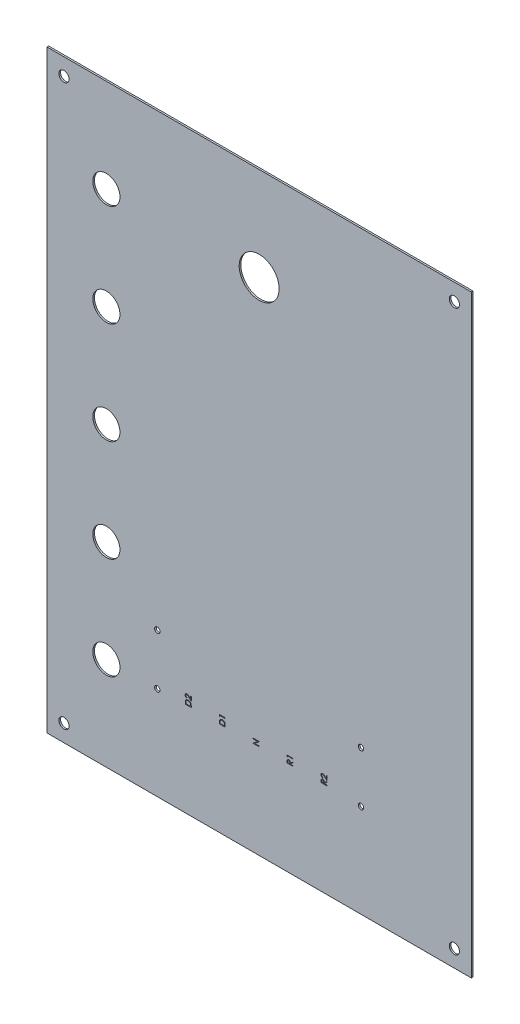
SolidWorks part; units mm, degrees
ref_plane "Front Plane" through (0, 0, 0) normal (1, 0, 0) x (0, 1, 0)
ref_plane "Top Plane" through (0, 0, 0) normal (0, 0, 1) x (0, 1, 0)
ref_plane "Right Plane" through (0, 0, 0) normal (0, 1, 0) x (-1, 0, 0)
sketch "Sketch1" plane through (0, 0, 0) normal (0, 0, 1) x (0, 1, 0)
  line L1 (-175, -125) -> (175, -125)
  line L2 (-175, -125) -> (-175, 125)
  line L3 (-175, 125) -> (175, 125)
  line L4 (175, -125) -> (175, 125)
  line L5 (-175, -125) -> (175, 125) construction
  line L6 (-175, 125) -> (175, -125) construction
  point P0 (0, 0)
  dimension "D1" = 350
  dimension "D2" = 250
extrude "Boss-Extrude1" add sketch "Sketch1" along normal blind 1
sketch "Sketch2" plane through (0, 0, 1) normal (0, 0, 1) x (0, -1, 0)
  line L0 (-160, -125) -> (-160, 125) construction
  line L1 (-175, -125) -> (175, -125) construction
  line L2 (175, 125) -> (-175, 125) construction
  line L3 (-175, 125) -> (-175, -125) construction
  circle A0 centre (-160, -60) radius 8
  circle A1 centre (-160, -30) radius 8
  circle A2 centre (-160, 0) radius 8
  circle A3 centre (-160, 30) radius 8
  circle A4 centre (-160, 60) radius 8
  dimension "D1" = 16
  dimension "D2" = 30
  dimension "D3" = 30
  dimension "D4" = 30
  dimension "D5" = 30
  dimension "D6" = 15
extrude "Cut-Extrude1" [suppressed] cut sketch "Sketch2" against normal through all
sketch "Sketch3" plane through (0, 0, 1) normal (0, 0, 1) x (0, -1, 0)
  line L0 (-175, -125) -> (175, -125) construction
  line L1 (-175, 125) -> (-175, -125) construction
  line L2 (0, 125) -> (0, -125) construction
  line L3 (175, 125) -> (-175, 125) construction
  line L4 (0, -125) -> (175, 0) construction
  line L5 (175, -125) -> (175, 125) construction
  line L6 (175, 0) -> (-175, 0) construction
  circle A0 centre (120, -90) radius 8
  circle A1 centre (60, -90) radius 8
  circle A2 centre (0, -90) radius 8
  circle A3 centre (-60, -90) radius 8
  circle A4 centre (-120, -90) radius 8
  circle A5 centre (-120, 0) radius 11.75
  circle A6 centre (-165, 115) radius 3
  circle A8 centre (165, 115) radius 3
  circle A9 centre (-165, -115) radius 3
  circle A10 centre (165, -115) radius 3
  point P7 (0, -125)
  point P18 (-175, 0)
  dimension "D1" = 16
  dimension "D3" = 23.5
  dimension "D5" = 6
  dimension "D6" = 10
  dimension "D4" = 5
  dimension "D2" = 35
  dimension "D7" = 10
extrude "Cut-Extrude2" cut sketch "Sketch3" against normal through all
sketch "Sketch4" plane through (0, 0, 1) normal (0, 0, 1) x (1, 0, 0)
  line L0 (-40, -120) -> (-40, -90) construction
  line L1 (60, -120) -> (-60, -120) construction
  line L2 (60, -120) -> (60, -90) construction
  line L3 (60, -90) -> (-60, -90) construction
  line L4 (-60, -120) -> (-60, -90) construction
  line L5 (60, -120) -> (-60, -90) construction
  line L6 (60, -90) -> (-60, -120) construction
  line L7 (-60, -105) -> (-40, -105) construction
  line L8 (-20, -120) -> (-20, -90) construction
  line L9 (-40, -105) -> (-20, -105) construction
  line L10 (0, -120) -> (0, -90) construction
  line L11 (-20, -105) -> (0, -105) construction
  line L12 (20, -120) -> (20, -90) construction
  line L13 (0, -105) -> (20, -105) construction
  line L14 (40, -120) -> (40, -90) construction
  line L15 (20, -105) -> (40, -105) construction
  line L16 (40, -105) -> (60, -105) construction
  circle A0 centre (-60, -90) radius 1.6
  circle A1 centre (-60, -120) radius 1.6
  circle A2 centre (60, -120) radius 1.6
  circle A3 centre (60, -90) radius 1.6
  circle A4 centre (-90, -120) radius 8 construction
  circle A5 centre (-90, -120) radius 8 construction
  text T0 "<b>N</b>"
  text T1 "<b>D1</b>"
  text T2 "<b>D2</b>"
  text T3 "R1"
  text T4 "<b>R2</b>"
  point P0 (0, -105)
  point P23 (-30, -105)
  point P30 (0, 0)
  point P31 (0, 0)
  dimension "D3" = 3.2
  dimension "D1" = 30
  dimension "D2" = 120
extrude "Cut-Extrude5" cut sketch "Sketch4" against normal through all
